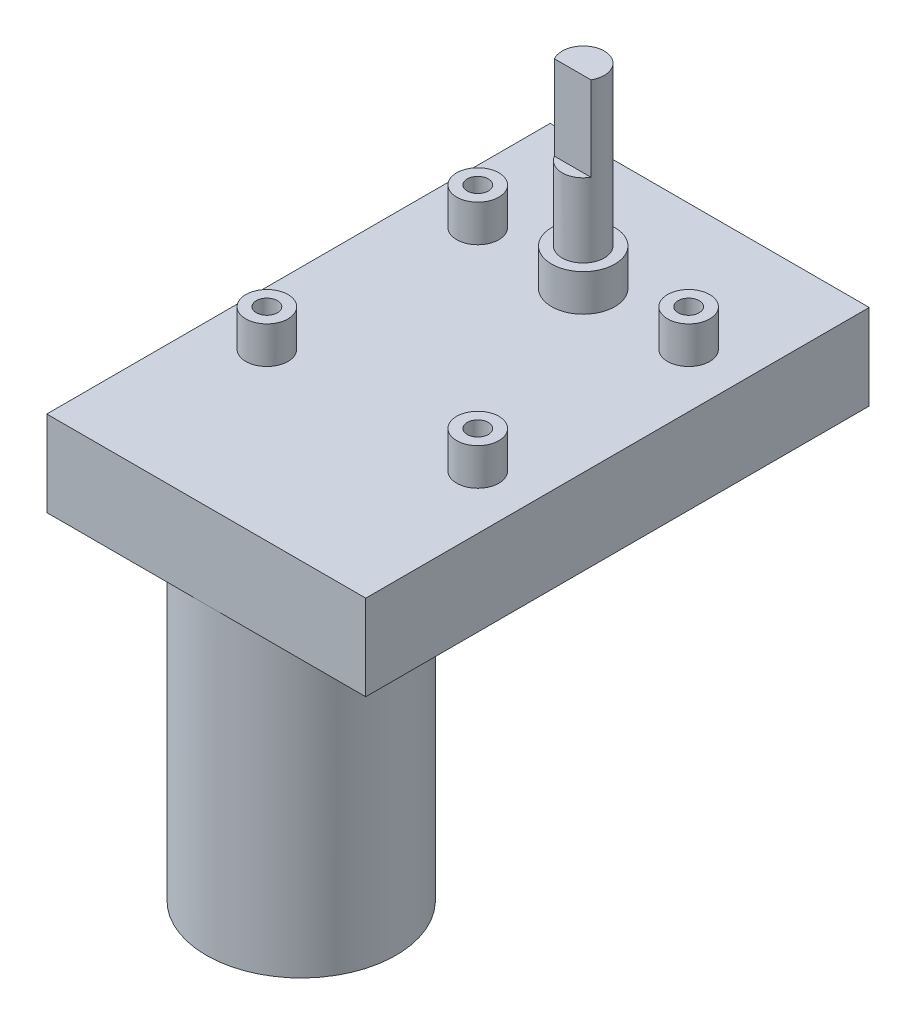
SolidWorks part; units mm, degrees
ref_plane "前视基准面" through (0, 0, 0) normal (0, 0, 1) x (1, 0, 0)
ref_plane "上视基准面" through (0, 0, 0) normal (0, 1, 0) x (1, 0, 0)
ref_plane "右视基准面" through (0, 0, 0) normal (1, 0, 0) x (0, 0, -1)
sketch "草图1" plane through (0, 0, 0) normal (0, 1, 0) x (1, 0, 0)
  line L0 (0, -338.6837) -> (0, 16595.4995) construction
  line L1 (-30.25, -71.5) -> (30.25, -71.5)
  line L2 (-30.25, -71.5) -> (-30.25, 24)
  line L3 (-30.25, 24) -> (30.25, 24)
  line L4 (30.25, -71.5) -> (30.25, 24)
  line L5 (-338.6837, 0) -> (16595.4995, 0) construction
  point P5 (0, 24)
  point P8 (30.25, -65.5515)
  dimension "D1" = 24
  dimension "D2" = 60.5
  dimension "D4" = 95.5
extrude "凸台-拉伸1" add sketch "草图1" along normal blind 16.2 contours L3 L4 L1 L2
sketch "草图2" plane through (0, 16.2, 0) normal (0, 1, 0) x (1, 0, 0)
  line L0 (-1000, 0) -> (49000, 0) construction
  line L1 (-1000.156, -40) -> (48999.844, -40) construction
  line L2 (0, -1000) -> (0, 49000) construction
  line L3 (-20, 0) -> (-20, -40) construction
  circle A0 centre (0, 0) radius 6
  circle A1 centre (-20, 0) radius 2
  circle A2 centre (20, 0) radius 2
  circle A3 centre (20, -40) radius 2
  circle A4 centre (-20, -40) radius 2
  circle A5 centre (-20, 0) radius 4
  circle A6 centre (20, 0) radius 4
  circle A7 centre (20, -40) radius 4
  circle A8 centre (-20, -40) radius 4
  dimension "D2" = 4
  dimension "D3" = 4
  dimension "D5" = 12
  dimension "D6" = 8
  dimension "D7" = 8
  dimension "D1" = 40
  dimension "D4" = 40
extrude "凸台-拉伸2" add sketch "草图2" along normal blind 7
sketch "草图3" plane through (0, 23.2, 0) normal (0, 1, 0) x (1, 0, 0)
  circle A0 centre (0, 0) radius 4
  dimension "D1" = 8
extrude "凸台-拉伸3" add sketch "草图3" along normal blind 30
sketch "草图4" plane through (0, 53.2, 0) normal (0, 1, 0) x (1, 0, 0)
  line L0 (-3.4641, -2) -> (3.4641, -2)
  circle A0 centre (0, 0) radius 4 construction
  arc A1 (-3.4641, -2) -> (3.4641, -2) centre (0, 0) ccw
  point P5 (0, 0)
  point P6 (0, 0)
  dimension "D1" = 2
extrude "切除-拉伸1" cut sketch "草图4" against normal blind 16
sketch "草图5" plane through (0, 0, 0) normal (0, -1, 0) x (-1, 0, 0)
  line L1 (17.5, 12.5) -> (-17.5, 12.5) construction
  line L2 (17.5, 12.5) -> (17.5, -12.5) construction
  line L3 (17.5, -12.5) -> (-17.5, -12.5) construction
  line L4 (-17.5, 12.5) -> (-17.5, -12.5) construction
  line L5 (17.5, 12.5) -> (-17.5, -12.5) construction
  line L6 (17.5, -12.5) -> (-17.5, 12.5) construction
  circle A0 centre (17.5, -12.5) radius 2
  circle A1 centre (-17.5, -12.5) radius 2
  circle A2 centre (-17.5, 12.5) radius 2
  circle A3 centre (17.5, 12.5) radius 2
  circle A4 centre (-17.5, 12.5) radius 4
  circle A5 centre (17.5, 12.5) radius 4
  circle A6 centre (17.5, -12.5) radius 4
  circle A7 centre (-17.5, -12.5) radius 4
  point P0 (0, 0)
  dimension "D3" = 4
  dimension "D4" = 4
  dimension "D5" = 4
  dimension "D6" = 4
  dimension "D7" = 8
  dimension "D8" = 8
  dimension "D9" = 8
  dimension "D10" = 8
  dimension "D1" = 35
  dimension "D2" = 25
extrude "凸台-拉伸4" add sketch "草图5" along normal blind 8
sketch "草图6" plane through (0, 0, 0) normal (0, -1, 0) x (1, 0, 0)
  line L0 (0, 53.5) -> (0, 0) construction
  line L1 (-30.25, 71.5) -> (30.25, 71.5) construction
  circle A0 centre (0, 53.5) radius 18
  dimension "D1" = 36
extrude "凸台-拉伸5" add sketch "草图6" along normal blind 57.6
